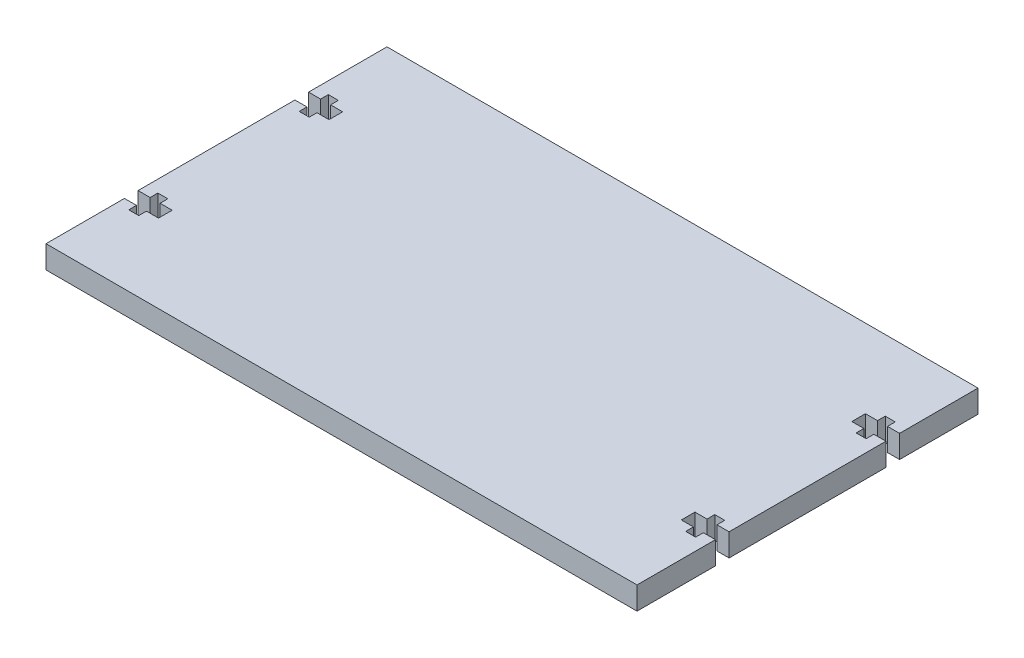
SolidWorks part; units mm, degrees
ref_plane "Front Plane" through (0, 0, 0) normal (0, 0, 1) x (1, 0, 0)
ref_plane "Top Plane" through (0, 0, 0) normal (0, 1, 0) x (1, 0, 0)
ref_plane "Right Plane" through (0, 0, 0) normal (1, 0, 0) x (0, 0, -1)
sketch "Sketch1" plane through (0, 0, 0) normal (0, 1, 0) x (1, 0, 0)
  line L1 (-82.55, -47.625) -> (82.55, -47.625)
  line L2 (-82.55, -47.625) -> (-82.55, 47.625)
  line L3 (-82.55, 47.625) -> (82.55, 47.625)
  line L4 (82.55, -47.625) -> (82.55, 47.625)
  line L5 (-82.55, -47.625) -> (82.55, 47.625) construction
  line L6 (-82.55, 47.625) -> (82.55, -47.625) construction
  point P0 (0, 0)
  dimension "D1" = 165.1
  dimension "D2" = 95.25
extrude "Boss-Extrude1" add sketch "Sketch1" along normal blind 6.35
sketch "Sketch2" plane through (0, 6.35, 0) normal (0, 1, 0) x (1, 0, 0)
  line L0 (82.55, -23.8125) -> (-82.55, -23.8125) construction
  line L1 (82.55, -47.625) -> (82.55, 47.625) construction
  line L2 (-82.55, 47.625) -> (-82.55, -47.625) construction
  line L3 (82.55, 0) -> (-82.55, 0) construction
  line L5 (-82.55, -47.625) -> (82.55, -47.625) construction
  line L6 (82.55, -21.9075) -> (82.55, -25.7175)
  line L11 (82.55, -25.7175) -> (79.1845, -25.7175)
  line L12 (82.55, -21.9075) -> (79.1845, -21.9075)
  line L13 (79.1845, -25.7175) -> (79.1845, -27.8765)
  line L14 (79.1845, -21.9075) -> (79.1845, -19.7485)
  line L15 (79.1845, -27.8765) -> (76.3905, -27.8765)
  line L16 (79.1845, -19.7485) -> (76.3905, -19.7485)
  line L17 (76.3905, -27.8765) -> (76.3905, -25.7175)
  line L18 (76.3905, -19.7485) -> (76.3905, -21.9075)
  line L19 (76.3905, -25.7175) -> (73.025, -25.7175)
  line L20 (76.3905, -21.9075) -> (73.025, -21.9075)
  line L21 (73.025, -25.7175) -> (73.025, -21.9075)
  point P12 (82.55, -25.7175)
  point P26 (73.025, -23.8125)
  dimension "D1" = 23.8125
  dimension "D2" = 9.525
  dimension "D3" = 3.81
  dimension "D4" = 4.064
  dimension "D7" = 2.794
extrude "Cut-Extrude1" cut sketch "Sketch2" against normal through all
mirror "Mirror1" about plane through (0, 0, 0) normal (0, 0, 1) of "Cut-Extrude1"
mirror "Mirror2" about plane through (0, 0, 0) normal (1, 0, 0) of "Mirror1", "Cut-Extrude1"
